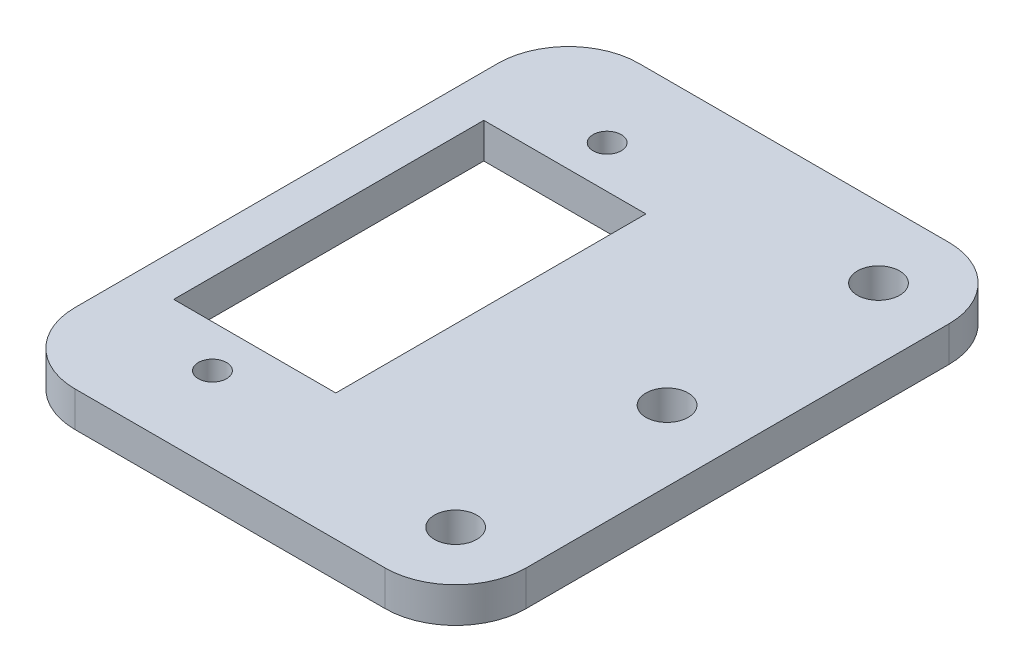
SolidWorks part; units mm, degrees
material "Acrylic (Medium-high impact)"
ref_plane "Front Plane" through (0, 0, 0) normal (0, 0, 1) x (1, 0, 0)
ref_plane "Top Plane" through (0, 0, 0) normal (0, 1, 0) x (1, 0, 0)
ref_plane "Right Plane" through (0, 0, 0) normal (1, 0, 0) x (0, 0, -1)
sketch "Sketch1" plane through (0, 0, 0) normal (0, 1, 0) x (1, 0, 0)
  line L0 (-16, 0) -> (16, 0) construction
  line L1 (-16, 20) -> (16, 20)
  line L2 (-16, 20) -> (-16, -20)
  line L3 (-16, -20) -> (16, -20)
  line L4 (16, 20) -> (16, -20)
  line L5 (0, -20) -> (0, 20) construction
  line L6 (-7.25, -11) -> (-7.25, -14) construction
  line L7 (-13, 11) -> (-1.5, 11)
  line L8 (-13, 11) -> (-13, -11)
  line L9 (-13, -11) -> (-1.5, -11)
  line L10 (-1.5, 11) -> (-1.5, -11)
  circle A0 centre (11, 15) radius 1.5
  circle A1 centre (11, 0) radius 1.5
  circle A2 centre (11, -15) radius 1.5
  circle A3 centre (-7.25, -14) radius 1
  circle A4 centre (-7.25, 14) radius 1
  point P10 (0, 0)
  point P23 (-13, 0)
  dimension "D3" = 3
  dimension "D10" = 2
  dimension "D1" = 32
  dimension "D2" = 40
  dimension "D5" = 5
  dimension "D6" = 22
  dimension "D7" = 11.5
  dimension "D8" = 12.5
  dimension "D9" = 3
  dimension "D4" = 3
extrude "Boss-Extrude1" add sketch "Sketch1" along normal blind 2.5
fillet "Fillet1" radius 5 4 edges at (-16, 1.25, -20) (16, 1.25, -20) (16, 1.25, 20) (-16, 1.25, 20)
